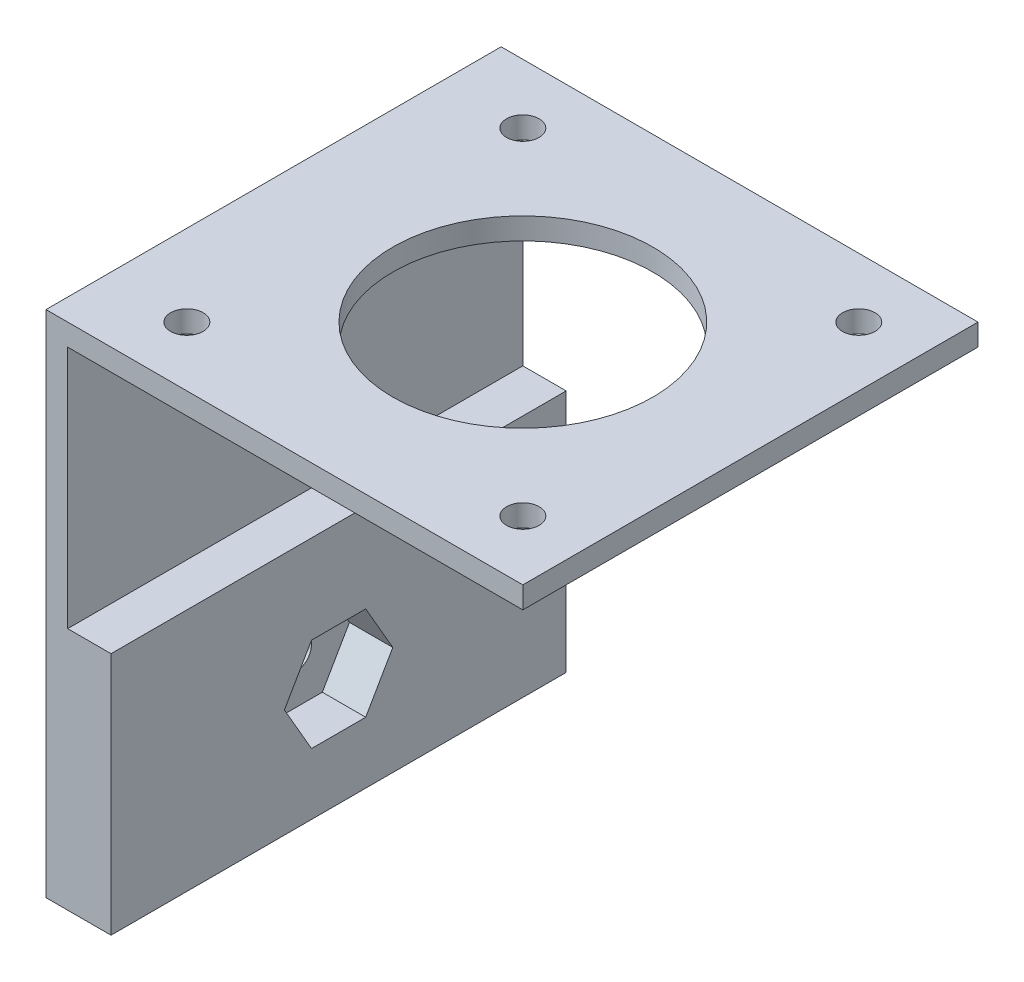
SolidWorks part; units mm, degrees
material "5052-H36"
ref_plane "前视基准面" through (0, 0, 0) normal (0, 0, 1) x (1, 0, 0)
ref_plane "上视基准面" through (0, 0, 0) normal (0, 1, 0) x (1, 0, 0)
ref_plane "右视基准面" through (0, 0, 0) normal (1, 0, 0) x (0, 0, -1)
sketch "草图1" plane through (0, 0, 0) normal (0, 1, 0) x (1, 0, 0)
  line L1 (0, 0) -> (42, 0)
  line L2 (0, 0) -> (0, 42)
  line L3 (0, 42) -> (42, 42)
  line L4 (42, 0) -> (42, 42)
extrude "凸台-拉伸1" add sketch "草图1" along normal blind 2
sketch "草图2" plane through (0, 2, 0) normal (0, 1, 0) x (1, 0, 0)
  circle A0 centre (21, 21) radius 12
  circle A1 centre (36.5, 36.5) radius 1.5
  circle A2 centre (36.5, 5.5) radius 1.5
  circle A3 centre (5.5, 5.5) radius 1.5
  circle A4 centre (5.5, 36.5) radius 1.5
extrude "切除-拉伸1" cut sketch "草图2" against normal blind 2
sketch "草图3" plane through (0, 0, 0) normal (-1, 0, 0) x (0, 0, 1)
  line L0 (-42, 2) -> (0, 2)
  line L1 (-42, 2) -> (0, 2) construction
  line L2 (0, 2) -> (0, 0)
  line L3 (0, 0) -> (-42, 0)
  line L4 (-42, 0) -> (-42, 2)
extrude "凸台-拉伸3" add sketch "草图3" along normal blind 2
sketch "草图4" plane through (0, 0, 0) normal (0, -1, 0) x (1, 0, 0)
  line L0 (-2, 0) -> (0, 0)
  line L1 (-2, 0) -> (42, 0) construction
  line L2 (0, 0) -> (0, -42)
  line L3 (42, -42) -> (-2, -42) construction
  line L4 (0, -42) -> (-2, -42)
  line L5 (-2, -42) -> (-2, 0)
extrude "凸台-拉伸4" add sketch "草图4" along normal blind 45
sketch "草图5" plane through (0, 0, 0) normal (1, 0, 0) x (0, 0, -1)
  line L0 (21, 0) -> (21, -35)
  line L1 (0, -45) -> (42, -45)
  line L2 (42, 0) -> (0, 0) construction
  line L3 (42, -45) -> (42, -22.5)
  line L4 (42, -45) -> (42, 0) construction
  line L5 (42, -22.5) -> (0, -22.5)
  line L6 (0, -45) -> (0, 0) construction
  line L7 (0, -22.5) -> (0, -45)
extrude "凸台-拉伸5" add sketch "草图5" along normal blind 4
sketch "草图6" plane through (4, 0, 0) normal (1, 0, 0) x (0, 0, -1)
  line L0 (21, 0) -> (21, -35)
  line L1 (42, 0) -> (0, 0) construction
  line L3 (26, -35) -> (23.5, -30.6699)
  line L4 (23.5, -30.6699) -> (18.5, -30.6699)
  line L5 (18.5, -30.6699) -> (16, -35)
  line L6 (16, -35) -> (18.5, -39.3301)
  line L7 (18.5, -39.3301) -> (23.5, -39.3301)
  line L8 (23.5, -39.3301) -> (26, -35)
  circle A0 centre (21, -35) radius 4.3301 construction
extrude "切除-拉伸2" cut sketch "草图6" against normal blind 4
sketch "草图7" plane through (0, 0, 0) normal (1, 0, 0) x (0, 0, -1)
  line L0 (16, -35) -> (26, -35)
  circle A0 centre (21, -35) radius 1.5
extrude "切除-拉伸3" cut sketch "草图7" against normal blind 4 contours L0 A0 | L0 A0
